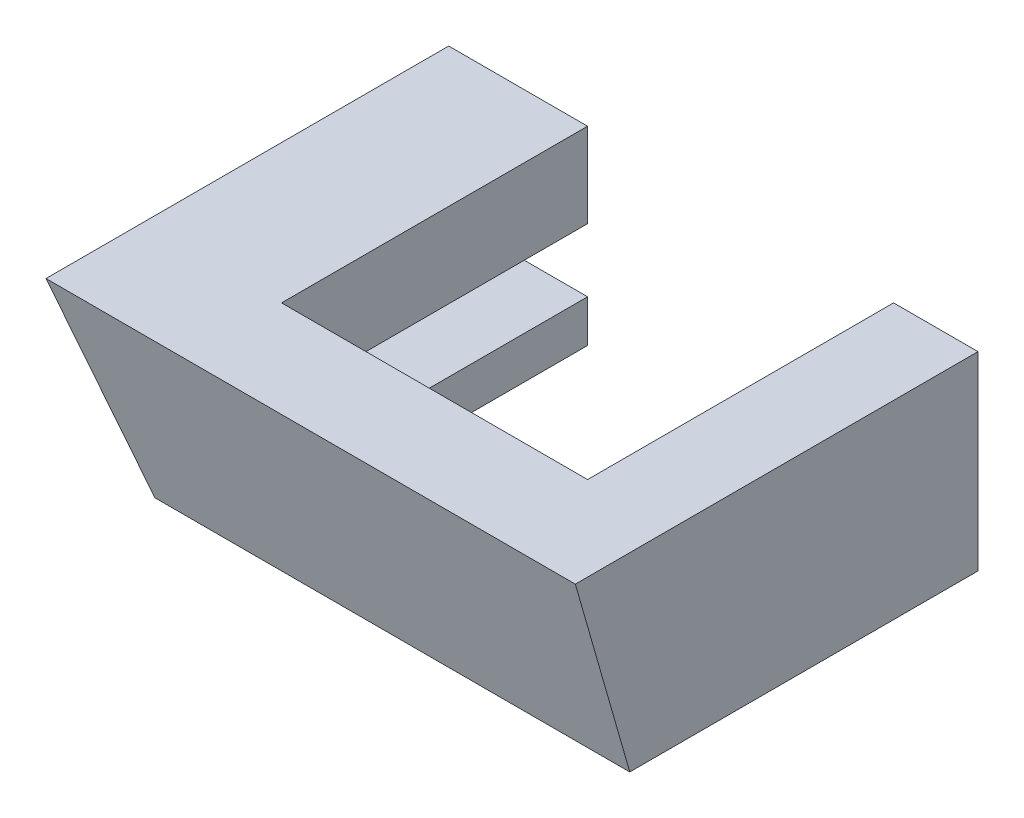
SolidWorks part; units mm, degrees
ref_plane "Front Plane" through (0, 0, 0) normal (0, 0, 1) x (1, 0, 0)
ref_plane "Top Plane" through (0, 0, 0) normal (0, 1, 0) x (1, 0, 0)
ref_plane "Right Plane" through (0, 0, 0) normal (1, 0, 0) x (0, 0, -1)
sketch "Sketch1" plane through (0, 0, 0) normal (0, 1, 0) x (1, 0, 0)
  line L4 (-45.0893, -57.125) -> (-22.5893, -57.125)
  line L5 (-22.5893, -57.125) -> (-22.5893, -40.625)
  line L6 (-22.5893, -40.625) -> (-45.0893, -40.625)
  line L7 (-45.0893, -40.625) -> (-45.0893, -57.125)
  dimension "D1" = 16.5
  dimension "D2" = 22.5
extrude "Boss-Extrude1" add sketch "Sketch1" along normal blind 9
sketch "Sketch3" plane through (0, 0, 0) normal (0, -1, 0) x (1, 0, 0)
  line L0 (-41.0893, 55.125) -> (-41.0893, 40.625)
  line L1 (-22.5893, 40.625) -> (-45.0893, 40.625) construction
  line L2 (-41.0893, 40.625) -> (-26.5893, 40.625)
  line L3 (-26.5893, 40.625) -> (-26.5893, 55.125)
  line L4 (-26.5893, 55.125) -> (-41.0893, 55.125)
  line L6 (-45.0893, 57.125) -> (-22.5893, 57.125) construction
  point P11 (-33.8393, 57.125)
  point P12 (-33.8393, 55.125)
  dimension "D1" = 2
  dimension "D2" = 14.5
extrude "Cut-Extrude2" cut sketch "Sketch3" against normal through all
draft "Draft1" type of draft neutral plane draft angle 16 faces to draft 1 face at (-45.0893, 4.5, 48.875) neutral plane through (0, 0, 0) neutral plane normal (0, -1, 0) parameters "D1"=16
draft "Draft3" type of draft neutral plane draft angle 16 faces to draft 1 face at (-34.4845, 4.5, 57.125) neutral plane through (0, 0, 0) neutral plane normal (0, -1, 0) parameters "D1"=16
sketch "Sketch9" plane through (0, 0, 40.625) normal (0, 0, 1) x (-1, 0, 0)
  line L0 (26.5893, -9) -> (26.5893, 0) construction
  line L1 (23.5893, -2) -> (26.5893, -2)
  line L2 (23.5893, -2) -> (23.5893, -5)
  line L3 (23.5893, -5) -> (26.5893, -5)
  line L4 (26.5893, -2) -> (26.5893, -5)
  line L5 (23.5893, -2) -> (26.5893, -5) construction
  line L6 (23.5893, -5) -> (26.5893, -2) construction
  line L7 (22.5893, -9) -> (26.5893, -9) construction
  line L8 (33.8393, -9) -> (33.8393, 0) construction
  line L10 (26.5893, 0) -> (41.0893, 0) construction
  line L11 (44.0893, -5) -> (41.0893, -2) construction
  line L12 (44.0893, -2) -> (41.0893, -5) construction
  line L13 (41.0893, -2) -> (41.0893, -5)
  line L14 (44.0893, -5) -> (41.0893, -5)
  line L15 (44.0893, -2) -> (44.0893, -5)
  line L16 (44.0893, -2) -> (41.0893, -2)
  line L18 (47.67, -9) -> (22.5893, -9) construction
  point P0 (25.0893, -3.5)
  point P10 (0, 0)
  point P15 (0, 0)
  point P21 (42.5893, -3.5)
  dimension "D1" = 3
  dimension "D2" = 3
  dimension "D3" = 4
extrude "Cut-Extrude3" cut sketch "Sketch9" along normal up to surface (14.5 mm away) up to face at (-33.8393, 4.5, 55.125)
